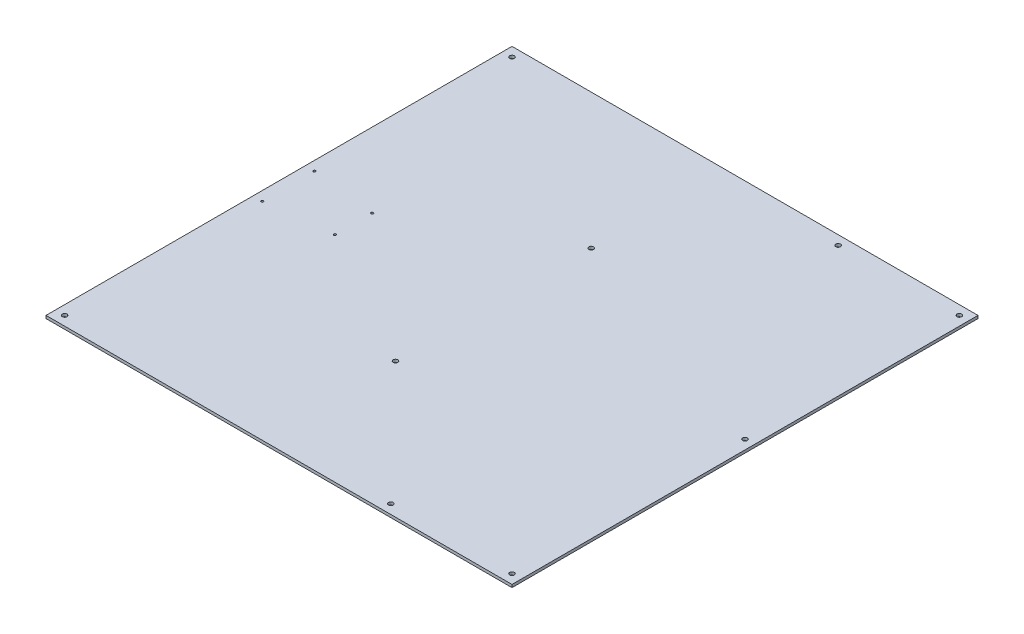
SolidWorks part; units mm, degrees
material "6063-O"
ref_plane "Front Plane" through (0, 0, 0) normal (0, 0, 1) x (1, 0, 0)
ref_plane "Top Plane" through (0, 0, 0) normal (0, 1, 0) x (1, 0, 0)
ref_plane "Right Plane" through (0, 0, 0) normal (1, 0, 0) x (0, 0, -1)
sketch "Sketch1" plane through (0, 0, 0) normal (0, 1, 0) x (1, 0, 0)
  line L1 (-250, 250) -> (250, 250)
  line L2 (-250, 250) -> (-250, -250)
  line L3 (-250, -250) -> (250, -250)
  line L4 (250, 250) -> (250, -250)
  line L5 (-250, 250) -> (250, -250) construction
  line L6 (-250, -250) -> (250, 250) construction
  point P0 (0, 0)
  dimension "D1" = 500
  dimension "D2" = 500
extrude "Boss-Extrude1" add sketch "Sketch1" along normal blind 3
sketch "Sketch2" plane through (0, 3, 0) normal (0, 1, 0) x (1, 0, 0)
  line L0 (-250, 250) -> (-250, -250) construction
  line L1 (250, 250) -> (-250, 250) construction
  line L2 (0, 250) -> (0, 0) construction
  line L3 (0, 0) -> (-250, 0) construction
  circle A0 centre (-240, 240) radius 2.5
  circle A1 centre (240, 240) radius 2.5
  circle A2 centre (240, -240) radius 2.5
  circle A3 centre (-240, -240) radius 2.5
  dimension "D1" = 5
  dimension "D2" = 10
  dimension "D3" = 10
extrude "Cut-Extrude1" cut sketch "Sketch2" against normal up to surface (3 mm away) up to face at (0, 0, 0)
sketch "Sketch3" plane through (0, 3, 0) normal (0, 1, 0) x (1, 0, 0)
  line L0 (-250, 250) -> (-250, -250) construction
  line L1 (250, 250) -> (-250, 250) construction
  line L2 (0, 0) -> (-250, 0) construction
  circle A0 centre (-240, 28) radius 1.25
  circle A1 centre (-170, 20) radius 1.25
  circle A2 centre (-170, -20) radius 1.25
  circle A3 centre (-240, -28) radius 1.25
  dimension "D1" = 2.5
  dimension "D2" = 2.5
  dimension "D3" = 8
  dimension "D4" = 70
  dimension "D5" = 10
  dimension "D6" = 222
extrude "Cut-Extrude2" cut sketch "Sketch3" against normal up to surface (3 mm away) up to face at (-240, 0, 242.5)
sketch "Sketch4" plane through (0, 3, 0) normal (0, 1, 0) x (1, 0, 0)
  line L0 (250, -250) -> (250, 250) construction
  line L1 (-250, -250) -> (250, -250) construction
  circle A0 centre (240, 10) radius 2.5
  circle A1 centre (240, 240) radius 2.5 construction
  circle A3 centre (110, 240) radius 2.5
  circle A7 centre (110, -240) radius 2.5
  dimension "D1" = 5
  dimension "D3" = 230
  dimension "D6" = 5
  dimension "D8" = 130
  dimension "D13" = 5
  dimension "D17" = 10
  dimension "D2" = 10
extrude "Cut-Extrude3" cut sketch "Sketch4" against normal up to surface (3 mm away) up to face at (-240, 0, -26.75)
sketch "Sketch5" plane through (0, 3, 0) normal (0, 1, 0) x (1, 0, 0)
  line L0 (-250, 250) -> (-250, -250) construction
  line L1 (250, 250) -> (-250, 250) construction
  line L2 (-250, -250) -> (250, -250) construction
  circle A0 centre (-20, 105) radius 2.5
  circle A1 centre (-20, -105) radius 2.5
  dimension "D1" = 5
  dimension "D2" = 5
  dimension "D3" = 230
  dimension "D4" = 145
  dimension "D5" = 145
extrude "Cut-Extrude4" cut sketch "Sketch5" against normal up to surface (3 mm away) up to face at (240, 0, -7.5)
